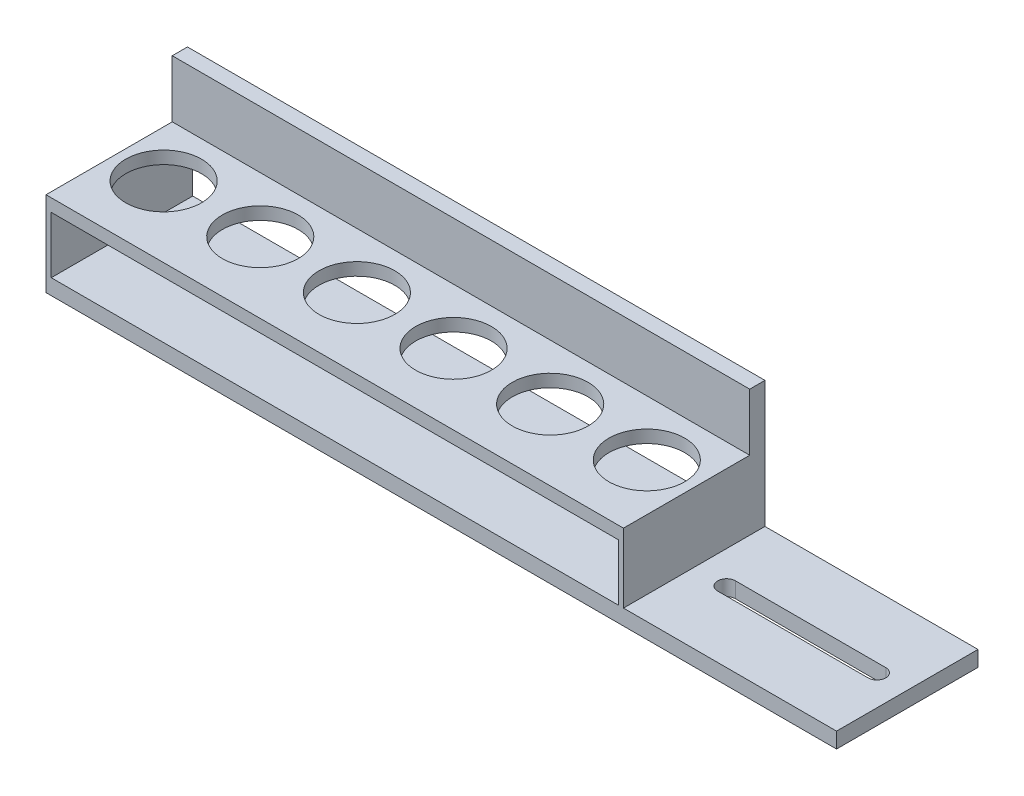
SolidWorks part; units mm, degrees
ref_plane "前视基准面" through (0, 0, 0) normal (0, 0, 1) x (1, 0, 0)
ref_plane "上视基准面" through (0, 0, 0) normal (0, 1, 0) x (1, 0, 0)
ref_plane "右视基准面" through (0, 0, 0) normal (1, 0, 0) x (0, 0, -1)
sketch "草图1" plane through (0, 0, 0) normal (0, 0, 1) x (1, 0, 0)
  line L1 (0, 0) -> (-228.6, 0)
  line L2 (0, 0) -> (0, 5)
  line L3 (0, 5) -> (-228.6, 5)
  line L4 (-228.6, 0) -> (-228.6, 5)
  dimension "D1" = 5
  dimension "D2" = 228.6
extrude "凸台-拉伸1" add sketch "草图1" along normal blind 56
sketch "草图2" plane through (0, 5, 0) normal (0, 1, 0) x (1, 0, 0)
  line L0 (-228.6, -28) -> (0, -28) construction
  line L1 (-228.6, -56) -> (-228.6, 0) construction
  line L2 (0, -56) -> (0, 0) construction
  circle A0 centre (-210.0391, -28) radius 15
  circle A1 centre (-171.7836, -28) radius 15
  circle A2 centre (-133.5282, -28) radius 15
  circle A3 centre (-95.2728, -28) radius 15
  circle A4 centre (-57.0174, -28) radius 15
  circle A5 centre (-18.762, -28) radius 15
  point P8 (-210.0391, -28)
  dimension "D1" = 30
  dimension "D2" = 6
extrude "切除-拉伸1" cut sketch "草图2" against normal blind 28
sketch "草图3" plane through (0, 5, 0) normal (0, 1, 0) x (1, 0, 0)
  line L0 (0, -56) -> (0, 0) construction
  line L1 (-228.6, 0) -> (0, 0)
  line L2 (-228.6, 0) -> (-228.6, -6.0229)
  line L3 (-228.6, -6.0229) -> (0, -6.0229)
  line L4 (0, 0) -> (0, -6.0229)
  line L5 (-228.6, -56) -> (-228.6, 0) construction
  point P7 (-228.6, -6.0229)
extrude "凸台-拉伸2" add sketch "草图3" along normal blind 22.666
sketch "草图4" plane through (0, 0, 0) normal (0, -1, 0) x (1, 0, 0)
  line L0 (-228.6, 56) -> (-228.6, 0) construction
  line L1 (-228.6, 56) -> (-228.6, 0)
  line L6 (0, 56) -> (0, 0)
  line L7 (-228.6, 56) -> (-226.5226, 56)
  line L8 (-228.6, 56) -> (0, 56) construction
  line L9 (-226.5226, 56) -> (-226.5226, 0)
  line L10 (-228.6, 0) -> (0, 0) construction
  line L11 (-226.5226, 0) -> (-228.6, 0)
  line L12 (0, 0) -> (-2.0049, 0)
  line L13 (-2.0049, 0) -> (-2.0049, 56)
  line L14 (-2.0049, 56) -> (0, 56)
extrude "凸台-拉伸3" add sketch "草图4" along normal blind 22.412
sketch "草图5" plane through (0, -22.412, 0) normal (0, -1, 0) x (1, 0, 0)
  line L0 (-228.6, 56) -> (-228.6, 0) construction
  line L1 (-228.6, 56) -> (-228.6, 0)
  line L2 (-226.5226, 56) -> (-2.0049, 56) construction
  line L3 (-226.5226, 56) -> (84.3402, 56)
  line L4 (-226.5226, 0) -> (-2.0049, 0) construction
  line L5 (-228.6, 0) -> (-226.5226, 0) construction
  line L6 (-226.5226, 56) -> (-228.6, 56) construction
  line L7 (-226.5226, 0) -> (84.3402, 0)
  line L8 (-228.6, 0) -> (-226.5226, 0)
  line L9 (-226.5226, 56) -> (-228.6, 56)
  line L10 (84.3402, 56) -> (84.3402, 0)
extrude "凸台-拉伸4" add sketch "草图5" along normal blind 6.156
sketch "草图7" plane through (0, -28.568, 0) normal (0, -1, 0) x (1, 0, 0)
  line L0 (84.3402, 28) -> (-10.3552, 28) construction
  line L1 (84.3402, 0) -> (84.3402, 56) construction
  line L2 (12.8104, 31.5133) -> (72.3366, 31.5133)
  line L4 (72.3366, 24.4867) -> (12.8104, 24.4867)
  arc A0 (72.3366, 24.4867) -> (72.3366, 31.5133) centre (72.3366, 28) ccw
  arc A1 (12.8104, 31.5133) -> (12.8104, 24.4867) centre (12.8104, 28) ccw
extrude "切除-拉伸2" cut sketch "草图7" against normal blind 6.156
